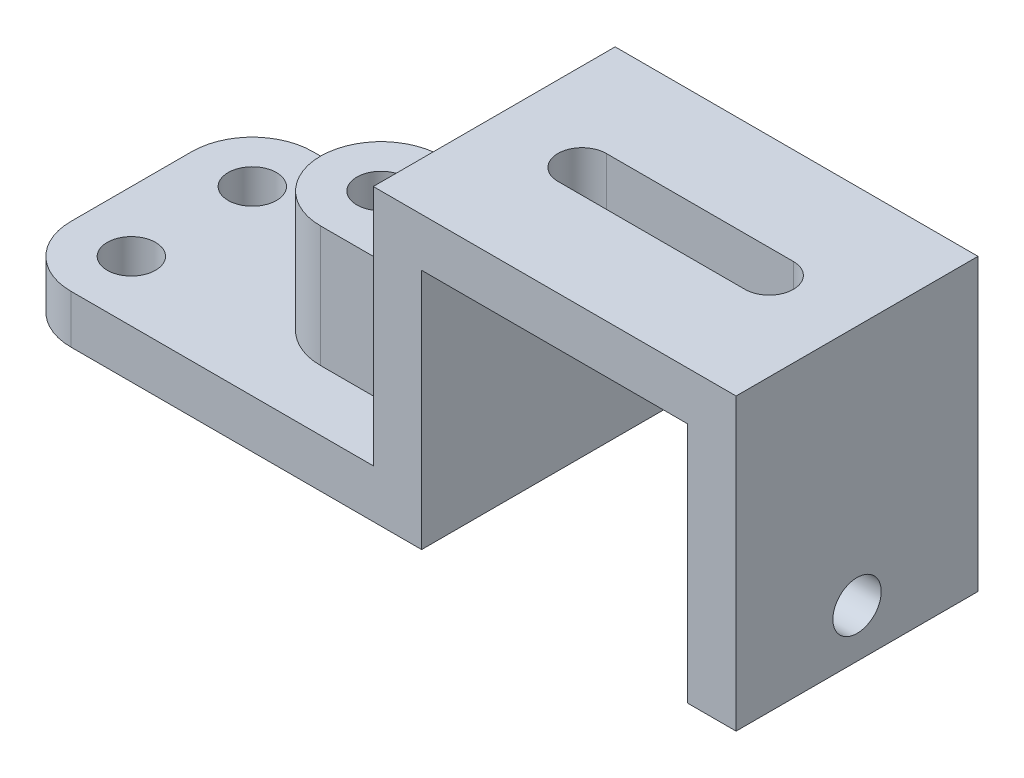
SolidWorks part; units mm, degrees
material "A-Glass Fiber"
ref_plane "Front Plane" through (0, 0, 0) normal (0, 0, 1) x (1, 0, 0)
ref_plane "Top Plane" through (0, 0, 0) normal (0, 1, 0) x (1, 0, 0)
ref_plane "Right Plane" through (0, 0, 0) normal (1, 0, 0) x (0, 0, -1)
sketch "Sketch1" plane through (0, 0, 0) normal (0, 0, 1) x (1, 0, 0)
  line L0 (-49.5, 0) -> (49.5, 0) construction
  line L1 (-67.5, 108) -> (67.5, 108)
  line L2 (67.5, 108) -> (67.5, 0)
  line L3 (67.5, 0) -> (49.5, 0)
  line L4 (49.5, 0) -> (49.5, 90)
  line L5 (49.5, 90) -> (-49.5, 90)
  line L6 (-49.5, 90) -> (-49.5, 0)
  line L7 (-49.5, 0) -> (-67.5, 0)
  line L8 (-67.5, 108) -> (-67.5, 18)
  line L9 (-67.5, 0) -> (-202.5, 0)
  line L10 (-202.5, 0) -> (-202.5, 18)
  line L11 (-202.5, 18) -> (-67.5, 18)
  point P5 (0, 108)
  dimension "D1" = 99
  dimension "D2" = 135
  dimension "D3" = 108
  dimension "D4" = 18
  dimension "D5" = 18
  dimension "D6" = 135
  dimension "D7" = 18
extrude "Boss-Extrude1" add sketch "Sketch1" along normal mid plane 90
fillet "Fillet1" radius 22.5 2 edges at (-202.5, 9, -45) (-202.5, 9, 45)
sketch "Sketch2" plane through (0, 18, 0) normal (0, 1, 0) x (1, 0, 0)
  circle A0 centre (-180, -22.5) radius 9
  circle A1 centre (-180, 22.5) radius 9
  arc A2 (-202.5, -22.5) -> (-180, -45) centre (-180, -22.5) ccw construction
  arc A3 (-180, 45) -> (-202.5, 22.5) centre (-180, 22.5) ccw construction
  dimension "D1" = 18
extrude "Cut-Extrude1" cut sketch "Sketch2" against normal blind 90
sketch "Sketch3" plane through (0, 18, 0) normal (0, 1, 0) x (1, 0, 0)
  line L0 (-67.5, 0) -> (-202.5, 0) construction
  line L1 (-67.5, -45) -> (-67.5, 45) construction
  line L2 (-202.5, -22.5) -> (-202.5, 22.5) construction
  line L3 (-67.5, 22.5) -> (-109.5967, 22.5)
  line L4 (-109.5967, 22.5) -> (-109.5967, -22.5) construction
  line L5 (-109.5967, -22.5) -> (-67.5, -22.5)
  line L6 (-67.5, -22.5) -> (-67.5, 22.5)
  arc A0 (-109.5967, 22.5) -> (-109.5967, -22.5) centre (-109.5967, 0) ccw
  circle A1 centre (-109.5967, 0) radius 9
  point P8 (-67.5, 0)
  point P11 (-109.5967, 0)
  dimension "D2" = 18
  dimension "D1" = 45
extrude "Boss-Extrude2" add sketch "Sketch3" along normal blind 45
sketch "Sketch4" plane through (0, 63, 0) normal (0, 1, 0) x (1, 0, 0)
  circle A0 centre (-109.5967, 0) radius 9 construction
  circle A3 centre (-109.5967, 0) radius 9
extrude "Cut-Extrude2" cut sketch "Sketch4" against normal through all
sketch "Sketch5" plane through (0, 108, 0) normal (0, 1, 0) x (1, 0, 0)
  line L0 (-34.8032, 0) -> (34.8032, 0) construction
  line L1 (-34.8032, 9) -> (34.8032, 9)
  line L2 (-34.8032, -9) -> (34.8032, -9)
  line L3 (67.5, 45) -> (-67.5, 45) construction
  arc A0 (-34.8032, 9) -> (-34.8032, -9) centre (-34.8032, 0) ccw
  arc A1 (34.8032, -9) -> (34.8032, 9) centre (34.8032, 0) ccw
  point P2 (0, 0)
  dimension "D1" = 18
  dimension "D2" = 36
extrude "Cut-Extrude3" cut sketch "Sketch5" against normal blind 45
sketch "Sketch6" plane through (67.5, 0, 0) normal (1, 0, 0) x (0, 0, -1)
  line L0 (45, 0) -> (45, 108) construction
  line L1 (-45, 0) -> (45, 0) construction
  circle A0 centre (0, 18) radius 9
  dimension "D1" = 18
  dimension "D2" = 45
  dimension "D3" = 18
extrude "Cut-Extrude4" cut sketch "Sketch6" against normal blind 45
